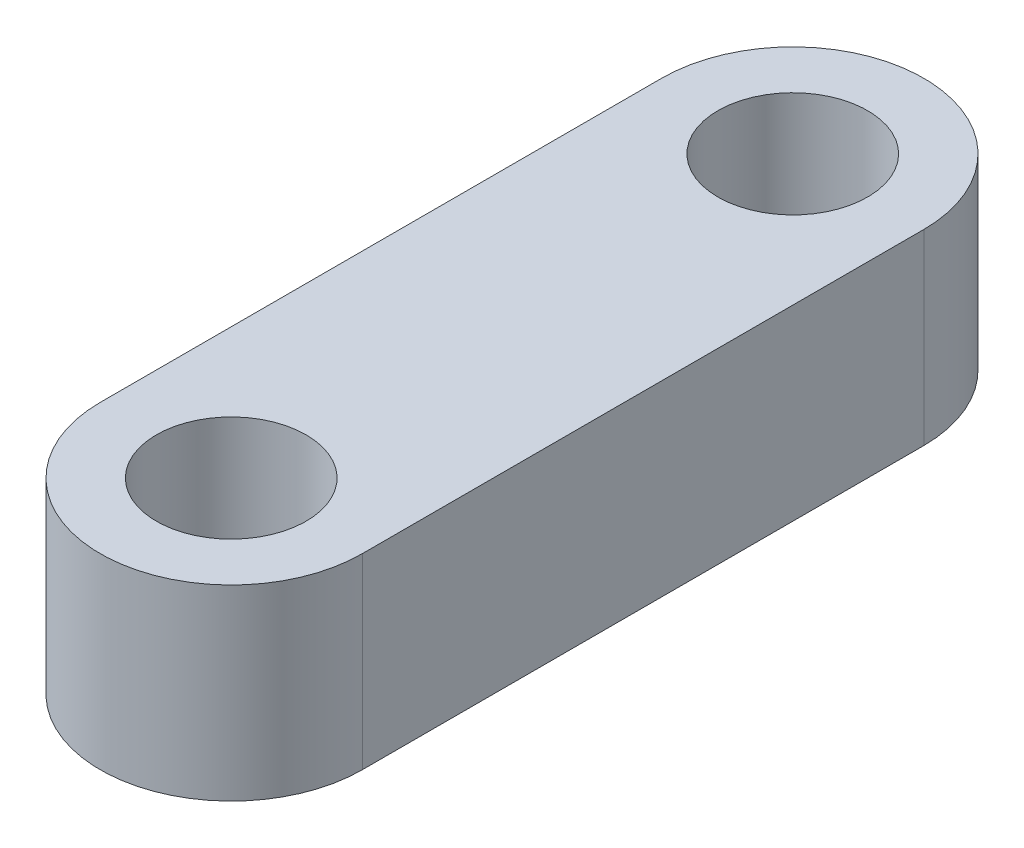
SolidWorks part; units mm, degrees
ref_plane "Front Plane" through (0, 0, 0) normal (0, 0, 1) x (1, 0, 0)
ref_plane "Top Plane" through (0, 0, 0) normal (0, 1, 0) x (1, 0, 0)
ref_plane "Right Plane" through (0, 0, 0) normal (1, 0, 0) x (0, 0, -1)
sketch "Sketch1" plane through (0, 0, 0) normal (0, 1, 0) x (1, 0, 0)
  line L0 (18.5, -42.0732) -> (11.5, -42.0732) construction
  line L1 (18.5, -57.0732) -> (11.5, -57.0732) construction
  line L2 (18.5, -42.0732) -> (18.5, -57.0732)
  line L4 (15, -49.5732) -> (26.7644, -49.5732) construction
  line L5 (11.5, -42.0732) -> (11.5, -57.0732)
  circle A1 centre (15, -42.0732) radius 2
  arc A2 (11.5, -42.0732) -> (18.5, -42.0732) centre (15, -42.0732) cw
  arc A4 (11.5, -57.0732) -> (18.5, -57.0732) centre (15, -57.0732) ccw
  circle A5 centre (15, -57.0732) radius 2
extrude "Boss-Extrude1" add sketch "Sketch1" along normal blind 5
